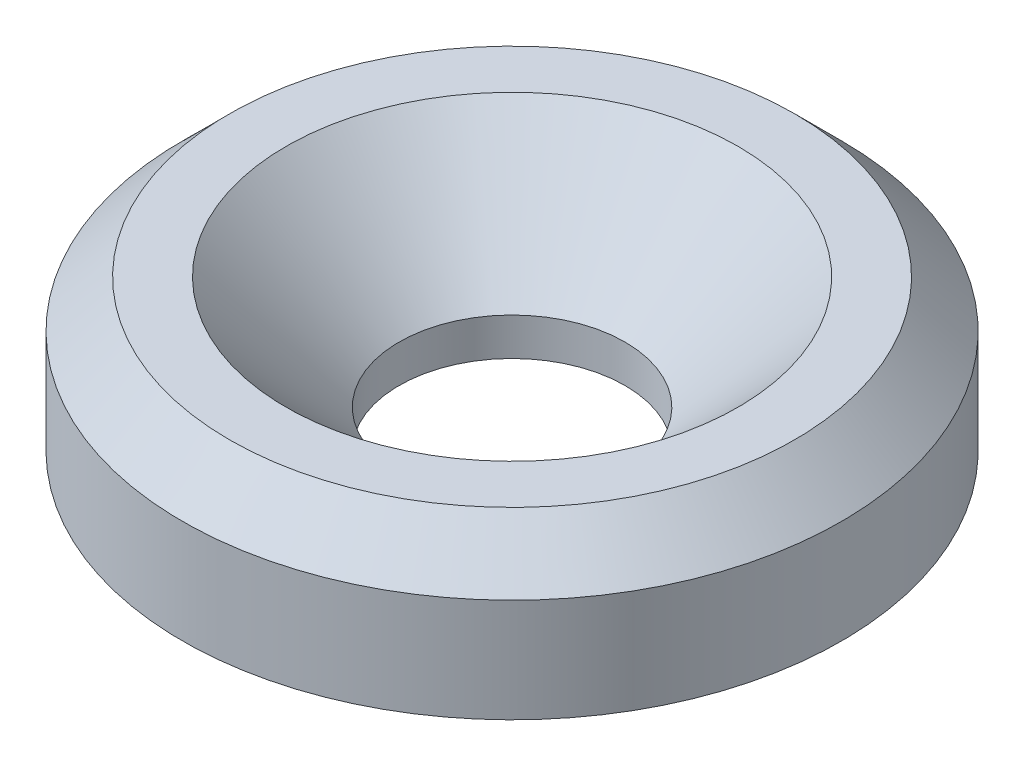
SolidWorks part; units mm, degrees
ref_plane "Front Plane" through (0, 0, 0) normal (0, 0, 1) x (1, 0, 0)
ref_plane "Top Plane" through (0, 0, 0) normal (0, 1, 0) x (1, 0, 0)
ref_plane "Right Plane" through (0, 0, 0) normal (1, 0, 0) x (0, 0, -1)
sketch "Sketch1" plane through (0, 0, 0) normal (0, 0, 1) x (1, 0, 0)
  line L0 (0, 0) -> (0, 23.0649) construction
  line L1 (-6, 0) -> (-6, 2)
  line L2 (-6, 2) -> (-12, 8)
  line L3 (-12, 8) -> (-17.5, 8)
  line L4 (-17.5, 8) -> (-17.5, 0)
  line L5 (-17.5, 0) -> (-6, 0)
  point P8 (-12.989, 8)
  dimension "D1" = 8
  dimension "D2" = 12
  dimension "D3" = 35
  dimension "D4" = 6
  dimension "D5" = 45
revolve "Revolve1" add sketch "Sketch1" angle 360 about L0
chamfer "Chamfer1" distance 2.5 angle 45 1 edges at (0, 8, -17.5)
